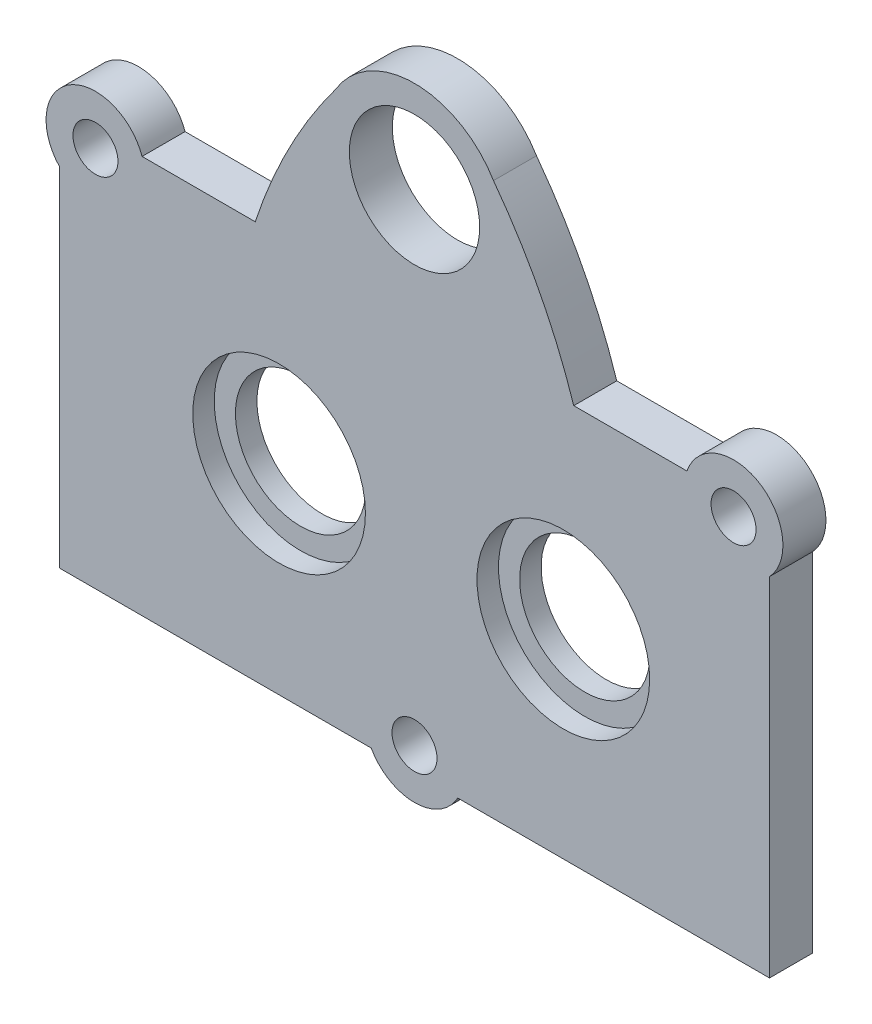
SolidWorks part; units mm, degrees
ref_plane "Front Plane" through (0, 0, 0) normal (0, 0, 1) x (1, 0, 0)
ref_plane "Top Plane" through (0, 0, 0) normal (0, 1, 0) x (1, 0, 0)
ref_plane "Right Plane" through (0, 0, 0) normal (1, 0, 0) x (0, 0, -1)
sketch "Sketch1" plane through (0, 0, 0) normal (0, 0, 1) x (1, 0, 0)
  line L1 (-26.416, -9.8) -> (26.416, -9.8)
  line L2 (-26.416, -9.8) -> (-26.416, 9.8)
  line L3 (-26.416, 9.8) -> (26.416, 9.8)
  line L4 (26.416, -9.8) -> (26.416, 9.8)
  line L5 (-26.416, -9.8) -> (26.416, 9.8) construction
  line L6 (-26.416, 9.8) -> (26.416, -9.8) construction
  line L7 (-20.15, -9.8) -> (20.15, -9.8)
  line L8 (-20.15, -9.8) -> (-20.15, 9.8)
  line L9 (-20.15, 9.8) -> (20.15, 9.8)
  line L10 (20.15, -9.8) -> (20.15, 9.8)
  line L11 (-20.15, -9.8) -> (20.15, 9.8) construction
  line L12 (-20.15, 9.8) -> (20.15, -9.8) construction
  line L13 (-26.416, 9.8) -> (26.416, 9.8)
  line L14 (-26.416, 9.8) -> (-26.416, 14.8)
  line L15 (-26.416, 14.8) -> (26.416, 14.8)
  line L16 (26.416, 9.8) -> (26.416, 14.8)
  line L17 (26.416, -9.8) -> (-26.416, -9.8)
  line L18 (26.416, -9.8) -> (26.416, -14.8)
  line L19 (26.416, -14.8) -> (-26.416, -14.8)
  line L20 (-26.416, -9.8) -> (-26.416, -14.8)
  circle A0 centre (-23.95, -4.974) radius 1.475
  circle A1 centre (-23.95, 4.974) radius 1.475
  circle A2 centre (23.95, 4.974) radius 1.475
  circle A3 centre (23.95, -4.974) radius 1.475
  point P0 (0, 0)
  point P14 (0, 0)
  dimension "D1" = 2.95
  dimension "D2" = 2.95
  dimension "D3" = 2.95
  dimension "D4" = 2.95
  dimension "D7" = 4.826
  dimension "D8" = 3.8
  dimension "D9" = 3.8
  dimension "D10" = 4.826
  dimension "D11" = 4.826
  dimension "D12" = 4.826
  dimension "D13" = 3.8
  dimension "D5" = 19.6
  dimension "D6" = 52.832
  dimension "D15" = 40.3
  dimension "D16" = 5
  dimension "D17" = 5
  dimension "3.9" = 3.8
extrude "Boss-Extrude2" add sketch "Sketch1" along normal blind 3.2 contours L1 L8 L3 L2 A1 A0 | L10 L1 L4 L3 A3 A2 | L14 L13 L16 L15 | L18 L17 L20 L19
sketch "Sketch3" plane through (0, 0, 0) normal (0, 0, -1) x (-1, 0, 0)
  line L3 (26.416, -14.8) -> (26.416, 14.8) construction
  line L4 (-26.416, -14.8) -> (26.416, -14.8) construction
  circle A0 centre (10.076, 0.11) radius 4.85
  circle A1 centre (10.076, 0.11) radius 6.85
  dimension "D1" = 16.34
  dimension "D2" = 14.91
  dimension "D4" = 9.7
  dimension "D3" = 2
extrude "Boss-Extrude3" add sketch "Sketch3" along normal blind 5.975 separate body
sketch "Sketch5" plane through (0, 0, 0) normal (0, 0, 1) x (1, 0, 0)
  circle A0 centre (-10.076, 0.11) radius 6.85
extrude "Cut-Extrude2" cut sketch "Sketch5" against normal blind 2.4892
sketch "Sketch10" plane through (0, 0, -5.975) normal (0, 0, -1) x (-1, 0, 0)
  line L0 (26.416, 14.8) -> (-26.416, 14.8) construction
  line L1 (3.23, 0.11) -> (16.93, 0.11)
  line L2 (3.23, 0.11) -> (3.23, 14.8)
  line L3 (3.23, 14.8) -> (16.93, 14.8)
  line L4 (16.93, 0.11) -> (16.93, 14.8)
  line L5 (-26.416, -14.8) -> (26.416, -14.8) construction
  line L6 (3.23, 0.11) -> (16.93, 0.11)
  line L7 (3.23, 0.11) -> (3.23, -14.8)
  line L8 (3.23, -14.8) -> (16.93, -14.8)
  line L9 (16.93, 0.11) -> (16.93, -14.8)
  circle A0 centre (10.076, 0.11) radius 6.846
  circle M1 centre (10.076, 0.11) radius 6.85
extrude "Boss-Extrude10" add sketch "Sketch10" against normal up to surface (3.4858 mm away) contours L4 L3 L2 M1 | L9 L7 L8 M1
sketch "Sketch11" plane through (0, 0, -5.975) normal (0, 0, -1) x (-1, 0, 0)
  line L0 (16.93, -14.8) -> (16.93, 14.8) construction
  line L1 (3.23, 14.8) -> (16.93, 14.8)
  line L2 (3.23, 14.8) -> (3.23, 9.8)
  line L3 (3.23, 9.8) -> (16.93, 9.8)
  line L4 (16.93, 14.8) -> (16.93, 9.8)
  line L5 (20.15, 9.8) -> (-20.15, 9.8) construction
  line L6 (-26.416, -14.8) -> (26.416, -14.8) construction
  line L7 (16.93, -14.8) -> (3.23, -14.8)
  line L8 (16.93, -14.8) -> (16.93, -9.8)
  line L9 (16.93, -9.8) -> (3.23, -9.8)
  line L10 (3.23, -14.8) -> (3.23, -9.8)
  line L11 (-20.15, -9.8) -> (20.15, -9.8) construction
  line L12 (3.23, 0.3441) -> (3.23, 14.8) construction
extrude "Boss-Extrude11" add sketch "Sketch11" against normal up to surface (5.975 mm away) contours L2 L1 L4 L3 | L8 L7 L10 L9 up to face at (0, 0, 0)
sketch "Sketch15" plane through (0, 0, 0) normal (0, 0, -1) x (-1, 0, 0)
  line L1 (-26.416, 14.8) -> (26.416, 14.8)
  line L2 (-26.416, 14.8) -> (-26.416, -14.8)
  line L3 (-26.416, -14.8) -> (26.416, -14.8)
  line L4 (26.416, 14.8) -> (26.416, -14.8)
extrude "Boss-Extrude13" add sketch "Sketch15" against normal up to surface (3.2 mm away) up to face at (0, 0, 3.2)
sketch "Sketch18" plane through (0, 0, -5.975) normal (0, 0, -1) x (-1, 0, 0)
  circle A0 centre (10.076, 0.11) radius 4.85
extrude "Cut-Extrude9" cut sketch "Sketch18" against normal through all
sketch "Sketch17" plane through (0, 0, -5.975) normal (0, 0, -1) x (-1, 0, 0)
  line L1 (-4.4232, 20.263) -> (21.6377, 20.263)
  line L2 (-4.4232, 20.263) -> (-4.4232, -20.3227)
  line L3 (-4.4232, -20.3227) -> (21.6377, -20.3227)
  line L4 (21.6377, 20.263) -> (21.6377, -20.3227)
extrude "Cut-Extrude10" cut sketch "Sketch17" against normal up to surface (5.975 mm away) up to face at (-5.226, 0.11, 0)
sketch "Sketch12" plane through (0, 0, 3.2) normal (0, 0, 1) x (1, 0, 0)
  line L1 (-26.416, 14.8) -> (26.416, 14.8)
  line L2 (-26.416, 14.8) -> (-26.416, -14.8)
  line L3 (-26.416, -14.8) -> (26.416, -14.8)
  line L4 (26.416, 14.8) -> (26.416, -14.8)
extrude "Boss-Extrude12" add sketch "Sketch12" against normal up to surface (3.2 mm away) up to face at (0, 0, 0)
sketch "Sketch13" plane through (0, 0, 0) normal (0, 0, -1) x (-1, 0, 0)
  line L0 (26.416, 14.8) -> (-26.416, 14.8) construction
  line L1 (26.416, -14.8) -> (26.416, 14.8) construction
  circle A0 centre (10.076, 0.11) radius 4.85
  dimension "D1" = 14.69
  dimension "D2" = 16.34
  dimension "D3" = 9.7
extrude "Cut-Extrude3" cut sketch "Sketch13" against normal blind 10
sketch "Sketch19" plane through (0, 0, 3.2) normal (0, 0, 1) x (1, 0, 0)
  line L0 (-26.416, 14.8) -> (26.416, 14.8) construction
  line L1 (-26.416, -14.8) -> (-26.416, 14.8) construction
  line L2 (26.416, -14.8) -> (26.416, 14.8) construction
  line L3 (26.416, -14.8) -> (-26.416, -14.8) construction
  circle A0 centre (0, -13.025) radius 1.675
  circle A1 centre (-23.741, 13.587) radius 1.675
  circle A2 centre (23.741, 13.587) radius 1.675
  dimension "D1" = 3.35
  dimension "D2" = 3.35
  dimension "D3" = 3.35
  dimension "D4" = 1.213
  dimension "D5" = 2.675
  dimension "D6" = 2.675
  dimension "D7" = 1.213
  dimension "D8" = 1.775
extrude "Cut-Extrude11" cut sketch "Sketch19" against normal up to surface (3.2 mm away) contours A1 | A2 | A0 up to face at (-14.926, 0.11, 0)
sketch "Sketch20" plane through (0, 0, 3.2) normal (0, 0, 1) x (1, 0, 0)
  circle A0 centre (0, -13.025) radius 1.675
  circle A1 centre (0, -13.025) radius 3.675
  dimension "D1" = 2
extrude "Boss-Extrude14" add sketch "Sketch20" against normal up to surface (3.2 mm away) contours A1
sketch "Sketch21" plane through (0, 0, 0) normal (0, 0, -1) x (-1, 0, 0)
  circle A0 centre (-23.741, 13.587) radius 1.675
  circle A1 centre (23.741, 13.587) radius 1.675
  circle A2 centre (23.741, 13.587) radius 3.675
  circle A3 centre (-23.741, 13.587) radius 3.675
  dimension "D1" = 2
extrude "Boss-Extrude15" add sketch "Sketch21" against normal up to surface (3.2 mm away) contours A3 | A2 | A1 | A0 up to face at (0, 2.1924, 3.2)
sketch "Sketch27" plane through (0, 0, 3.2) normal (0, 0, 1) x (1, 0, 0)
  circle A0 centre (11.074, 0) radius 4.85
  circle A1 centre (-10.076, 0.11) radius 4.85 construction
  dimension "D1" = 9.7
  dimension "D2" = 21.15
extrude "Cut-Extrude18" cut sketch "Sketch27" against normal blind 188
sketch "Sketch30" plane through (0, 0, 3.2) normal (0, 0, 1) x (1, 0, 0)
  line L0 (-20.272, 14.8) -> (20.272, 14.8) construction
  line L1 (-6.85, 22.8) -> (-6.85, 14.8)
  line L2 (6.85, 22.8) -> (6.85, 14.8)
  circle A0 centre (0, 22.8) radius 4.85
  circle A1 centre (0, 22.8) radius 6.85
  line M5 (20.272, 14.8) -> (-20.272, 14.8)
  dimension "D1" = 9.7
  dimension "D2" = 8
  dimension "D3" = 2
extrude "Boss-Extrude17" add sketch "Sketch30" against normal up to surface (3.2 mm away) contours A1 A0 | A1 L1 L2 M5 up to face at (15.924, 0, 0)
sketch "Sketch31" plane through (0, 0, 3.2) normal (0, 0, 1) x (1, 0, 0)
  line L0 (6.85, 22.8) -> (0, 29.65)
  line L1 (0, 29.65) -> (-6.85, 22.8)
  line L2 (-3.425, 26.225) -> (-6.4007, 29.2007)
  line L3 (3.425, 26.225) -> (5.9804, 28.7804)
  line L4 (-6.85, 14.8) -> (-11.85, 14.8)
  line L5 (-20.272, 14.8) -> (-6.85, 14.8) construction
  line L6 (6.85, 14.8) -> (11.85, 14.8)
  line L7 (6.85, 14.8) -> (20.272, 14.8) construction
  line L8 (-6.85, 22.8) -> (-6.85, 14.8)
  line L9 (6.85, 22.8) -> (6.85, 14.8)
  arc A0 (6.85, 22.8) -> (-6.85, 22.8) centre (0, 22.8) ccw construction
  arc A1 (-11.85, 14.8) -> (-4.8437, 27.6437) centre (26.176, 2.3894) cw
  arc A2 (11.85, 14.8) -> (4.8437, 27.6437) centre (-26.176, 2.3894) ccw
  circle A3 centre (0, 22.8) radius 6.85
  line M5 (-6.85, 14.8) -> (-20.272, 14.8)
  line M13 (20.272, 14.8) -> (6.85, 14.8)
  line M14 (6.85, 14.8) -> (6.85, 22.8)
  arc M15 (6.85, 22.8) -> (-6.85, 22.8) centre (0, 22.8) ccw
  line M16 (-6.85, 22.8) -> (-6.85, 14.8)
  dimension "D3" = 40
  dimension "D4" = 40
  dimension "D1" = 5
  dimension "D2" = 5
extrude "Boss-Extrude18" add sketch "Sketch31" against normal up to surface (3.2 mm away) contours A1 M5 M16 M15 | A2 M13 M15 M14 up to face at (15.924, 0, 0)
sketch "Sketch32" plane through (0, 0, 3.2) normal (0, 0, 1) x (1, 0, 0)
  circle A0 centre (-10.076, 0.11) radius 6.425
  circle A1 centre (11.074, 0) radius 6.425
  dimension "D1" = 12.85
  dimension "D2" = 12.85
extrude "Cut-Extrude19" cut sketch "Sketch32" against normal blind 1.6
